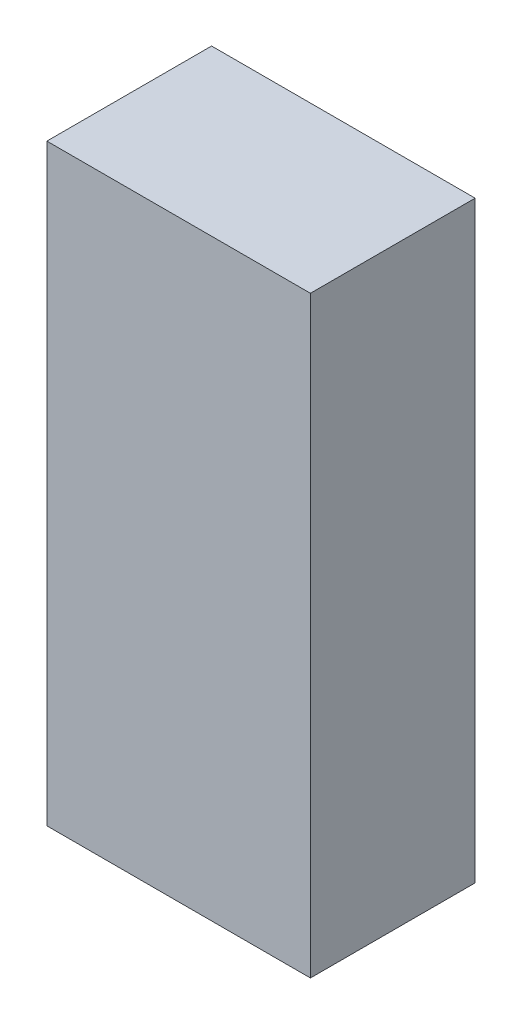
SolidWorks part; units mm, degrees
ref_plane "Front Plane" through (0, 0, 0) normal (0, 0, 1) x (1, 0, 0)
ref_plane "Top Plane" through (0, 0, 0) normal (0, 1, 0) x (1, 0, 0)
ref_plane "Right Plane" through (0, 0, 0) normal (1, 0, 0) x (0, 0, -1)
sketch "Sketch1" plane through (0, 0, 0) normal (0, 1, 0) x (1, 0, 0)
  line L1 (-12.7, -7.9375) -> (12.7, -7.9375)
  line L2 (-12.7, -7.9375) -> (-12.7, 7.9375)
  line L3 (-12.7, 7.9375) -> (12.7, 7.9375)
  line L4 (12.7, -7.9375) -> (12.7, 7.9375)
  line L5 (-12.7, -7.9375) -> (12.7, 7.9375) construction
  line L6 (-12.7, 7.9375) -> (12.7, -7.9375) construction
  point P0 (0, 0)
  dimension "D1" = 25.4
  dimension "D2" = 15.875
extrude "Boss-Extrude1" add sketch "Sketch1" along normal blind 57.15
